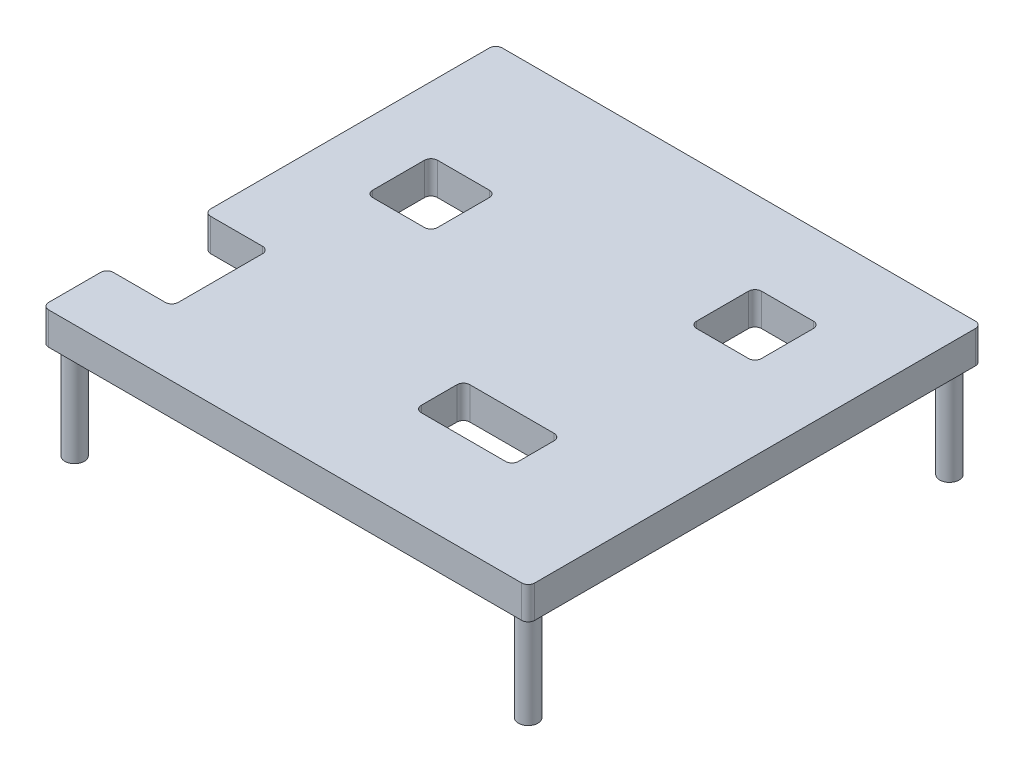
SolidWorks part; units mm, degrees
ref_plane "Front Plane" through (0, 0, 0) normal (0, 0, 1) x (1, 0, 0)
ref_plane "Top Plane" through (0, 0, 0) normal (0, 1, 0) x (1, 0, 0)
ref_plane "Right Plane" through (0, 0, 0) normal (1, 0, 0) x (0, 0, -1)
sketch "Sketch1" plane through (0, 0, 0) normal (0, 1, 0) x (1, 0, 0)
  line L1 (-75, 70) -> (75, 70)
  line L2 (-75, 70) -> (-75, -70)
  line L3 (-75, -70) -> (75, -70)
  line L4 (75, 70) -> (75, -70)
  point P4 (0, 70)
  point P6 (-75, 0)
  point P7 (0, -70)
  point P9 (75, 0)
  dimension "D1" = 150
  dimension "D2" = 140
extrude "Boss-Extrude1" add sketch "Sketch1" along normal blind 10 contours L1 L4 L3 L2
sketch "Sketch2" plane through (0, 0, 0) normal (0, -1, 0) x (1, 0, 0)
  line L0 (-75, 70) -> (75, 70) construction
  line L1 (-75, -70) -> (-75, 70) construction
  line L2 (75, -70) -> (75, 70) construction
  line L3 (-75, -70) -> (75, -70) construction
  circle A0 centre (-70, 65) radius 3
  circle A1 centre (70, 65) radius 3
  circle A2 centre (70, -65) radius 3
  circle A3 centre (-70, -65) radius 3
  dimension "D1" = 6
  dimension "D4" = 6
  dimension "D7" = 6
  dimension "D10" = 6
  dimension "D2" = 5
  dimension "D3" = 5
  dimension "D5" = 5
  dimension "D6" = 5
  dimension "D8" = 5
  dimension "D9" = 5
  dimension "D11" = 5
  dimension "D12" = 5
extrude "Boss-Extrude2" add sketch "Sketch2" along normal blind 30 contours A0 | A3 | A2 | A1
sketch "Sketch4" plane through (0, 10, 0) normal (0, 1, 0) x (1, 0, 0)
  line L0 (-75, 70) -> (-75, -70) construction
  line L5 (-35, 10) -> (-35, 30)
  line L6 (-35, 30) -> (-55, 30)
  line L7 (-35, 10) -> (-55, 10)
  line L8 (-55, 10) -> (-55, 30)
  line L9 (-75, 70) -> (75, 70) construction
  point P4 (-35, 10)
  point P10 (-55, 10)
  dimension "D1" = 20
  dimension "D2" = 60
  dimension "D3" = 40
  dimension "D4" = 40
extrude "Cut-Extrude2" cut sketch "Sketch4" against normal through all contours L7 L8 L6 L5
sketch "Sketch6" plane through (0, 10, 0) normal (0, 1, 0) x (1, 0, 0)
  line L0 (-75, 70) -> (-75, -70) construction
  line L1 (-75, -50) -> (-55, -50)
  line L2 (-75, -50) -> (-75, -20)
  line L3 (-75, -20) -> (-55, -20)
  line L4 (-55, -50) -> (-55, -20)
  dimension "D1" = 20
  dimension "D2" = 50
  dimension "D3" = 20
extrude "Cut-Extrude3" cut sketch "Sketch6" against normal through all
sketch "Sketch7" plane through (0, 10, 0) normal (0, 1, 0) x (1, 0, 0)
  line L0 (-75, 70) -> (75, 70) construction
  line L1 (40, -40) -> (10, -40)
  line L2 (40, -40) -> (40, -25)
  line L3 (40, -25) -> (10, -25)
  line L4 (10, -40) -> (10, -25)
  line L6 (75, 70) -> (75, -70) construction
  dimension "D1" = 95
  dimension "D2" = 110
  dimension "D3" = 30
  dimension "D4" = 35
extrude "Cut-Extrude4" cut sketch "Sketch7" against normal through all contours L1 L4 L3 L2
sketch "Sketch8" plane through (0, 10, 0) normal (0, 1, 0) x (1, 0, 0)
  line L0 (75, 70) -> (75, -70) construction
  line L1 (30, 25) -> (50, 25)
  line L2 (30, 25) -> (30, 45)
  line L3 (30, 45) -> (50, 45)
  line L4 (50, 25) -> (50, 45)
  line L5 (-75, 70) -> (75, 70) construction
  dimension "D1" = 25
  dimension "D2" = 45
  dimension "D3" = 20
  dimension "D4" = 20
extrude "Cut-Extrude5" cut sketch "Sketch8" against normal through all
fillet "Fillet2" radius 2 20 edges at (30, 5, -45) (50, 5, -25) (30, 5, -25) (50, 5, -45) (-35, 5, -30) (-35, 5, -10) (-55, 5, -10) (-55, 5, -30) (10, 5, 25) (40, 5, 25) (40, 5, 40) (10, 5, 40) (-75, 5, 70) (-55, 5, 20) (-55, 5, 50) (-75, 5, 20) (-75, 5, 50) (-75, 5, -70) (75, 5, -70) (75, 5, 70)
